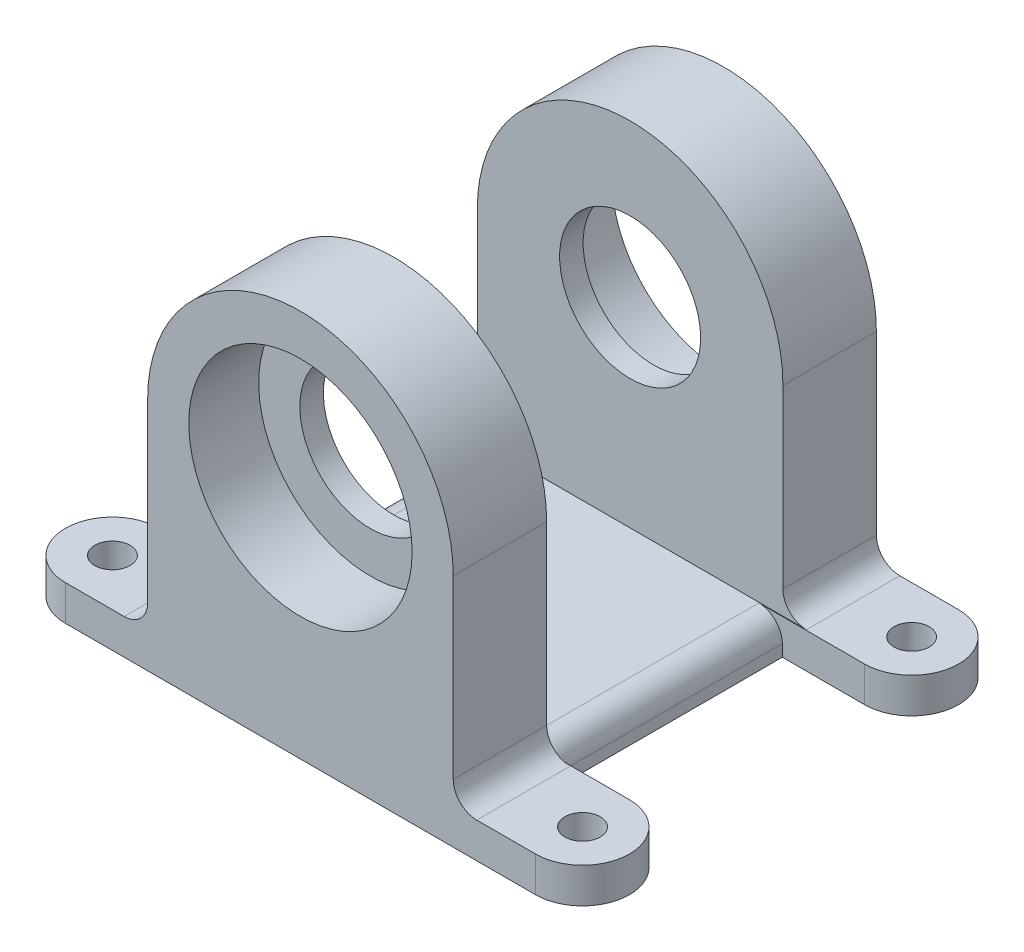
SolidWorks part; units mm, degrees
ref_plane "Alzado" through (0, 0, 0) normal (0, 0, 1) x (1, 0, 0)
ref_plane "Planta" through (0, 0, 0) normal (0, 1, 0) x (1, 0, 0)
ref_plane "Vista lateral" through (0, 0, 0) normal (1, 0, 0) x (0, 0, -1)
sketch "Croquis1" plane through (0, 0, 0) normal (0, 0, 1) x (1, 0, 0)
  line L0 (0, 0) -> (0, 17.6859) construction
  line L1 (0, 0) -> (-25.4426, 0) construction
  line L2 (-13, 0) -> (-13, -20)
  line L3 (-13, -20) -> (13, -20)
  line L4 (13, -20) -> (13, 0)
  circle A0 centre (0, 0) radius 9.5
  arc A1 (13, 0) -> (-13, 0) centre (0, 0) ccw
  dimension "D1" = 19
  dimension "D2" = 13
  dimension "D3" = 20
extrude "Saliente-Extruir1" add sketch "Croquis1" along normal blind 36
sketch "Croquis2" plane through (13, 0, 0) normal (1, 0, 0) x (0, 0, -1)
  line L0 (-18, -20) -> (-18, -29.3415) construction
  line L1 (-36, -20) -> (0, -20) construction
  line L4 (0, 13) -> (-36, 13) construction
  line L5 (-7.95, 13) -> (-28.05, 13)
  line L7 (-28.05, 13) -> (-28.05, -17)
  line L8 (-28.05, -17) -> (-7.95, -17)
  line L9 (-7.95, -17) -> (-7.95, 13)
  dimension "D1" = 20.1
  dimension "D2" = 3
extrude "Cortar-Extruir2" cut sketch "Croquis2" against normal through all
sketch "Croquis3" plane through (0, 0, 28.05) normal (0, 0, -1) x (-1, 0, 0)
  circle A0 centre (0, 0) radius 9.5
  circle A1 centre (0, 0) radius 6
  dimension "D1" = 19
  dimension "D2" = 12
extrude "Saliente-Extruir2" add sketch "Croquis3" against normal blind 2
sketch "Croquis4" plane through (0, 0, 7.95) normal (0, 0, 1) x (1, 0, 0)
  circle A0 centre (0, 0) radius 9.5 construction
  circle A1 centre (0, 0) radius 9.5
  circle A2 centre (0, 0) radius 6 construction
  circle A3 centre (0, 0) radius 6
extrude "Saliente-Extruir3" add sketch "Croquis4" against normal blind 2
sketch "Croquis5" plane through (0, -20, 0) normal (0, -1, 0) x (1, 0, 0)
  line L0 (13, 36) -> (20, 36)
  line L1 (20, 28) -> (13, 28)
  line L2 (13, 36) -> (13, 0) construction
  line L3 (13, 28) -> (13, 36)
  line L4 (13, 0) -> (20, 0)
  line L5 (20, 8) -> (13, 8)
  line L6 (13, 8) -> (13, 0)
  line L7 (0, 0) -> (0, -17.9347) construction
  line L8 (-13, 0) -> (-20, 0)
  line L9 (-20, 8) -> (-13, 8)
  line L10 (-13, 8) -> (-13, 0)
  line L11 (-13, 28) -> (-13, 36)
  line L12 (-13, 36) -> (-20, 36)
  line L13 (-20, 28) -> (-13, 28)
  arc A0 (20, 36) -> (20, 28) centre (20, 32) cw
  arc A1 (20, 0) -> (20, 8) centre (20, 4) ccw
  arc A2 (-20, 0) -> (-20, 8) centre (-20, 4) cw
  arc A3 (-20, 36) -> (-20, 28) centre (-20, 32) ccw
  dimension "D1" = 7
  dimension "D2" = 4
  dimension "D4" = 4
  dimension "D3" = 7
extrude "Saliente-Extruir4" add sketch "Croquis5" against normal blind 3
sketch "Croquis6" plane through (0, -20, 0) normal (0, -1, 0) x (1, 0, 0)
  circle A0 centre (-20, 32) radius 1.5
  circle A1 centre (20, 32) radius 1.5
  circle A2 centre (-20, 4) radius 1.5
  circle A3 centre (20, 4) radius 1.5
  dimension "D1" = 3
  dimension "D2" = 3
  dimension "D3" = 3
  dimension "D4" = 3
extrude "Cortar-Extruir3" cut sketch "Croquis6" against normal through all
fillet "Redondeo1" [suppressed] radius 3
fillet "Redondeo2" [suppressed] radius 3
fillet "Redondeo3" radius 2 6 edges at (-13, -17, 32.025) (-13, -17, 3.975) (-13, -17, 18) (13, -17, 3.975) (13, -17, 18) (13, -17, 32.025)
